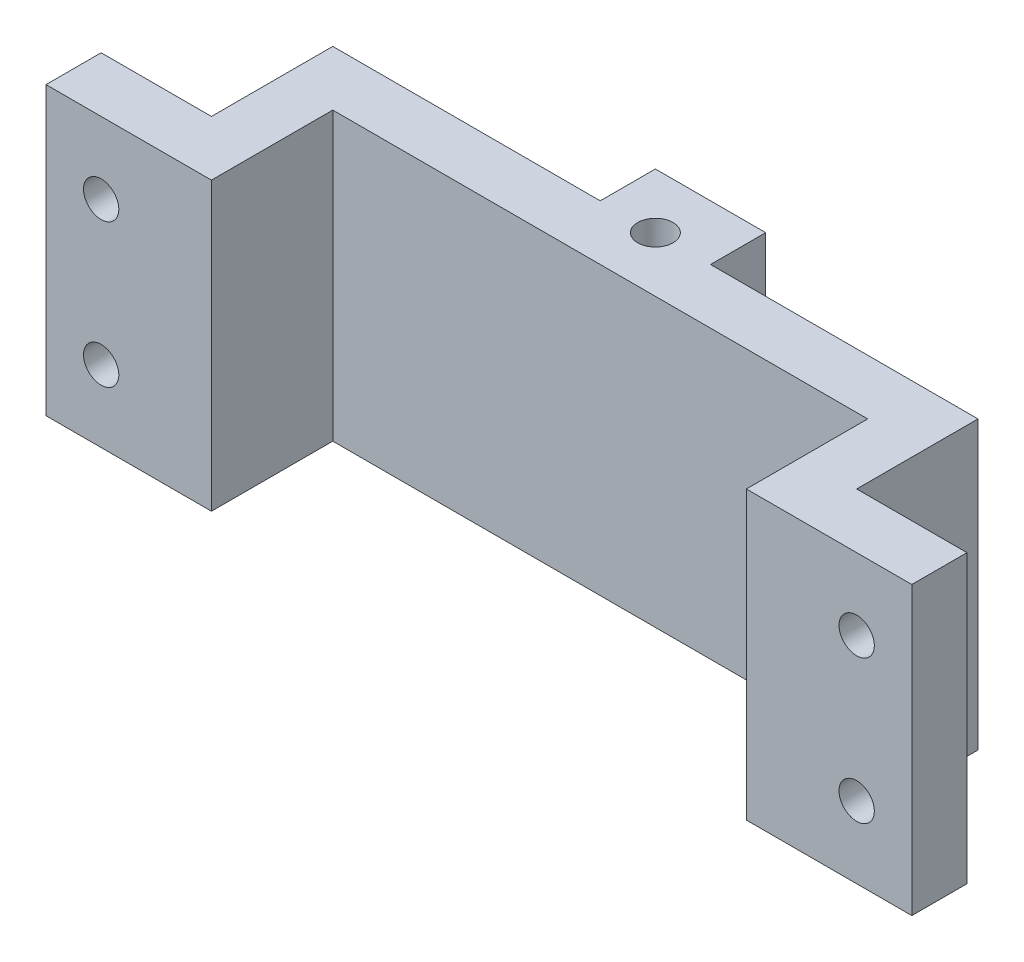
SolidWorks part; units mm, degrees
ref_plane "Front Plane" through (0, 0, 0) normal (0, 0, 1) x (1, 0, 0)
ref_plane "Top Plane" through (0, 0, 0) normal (0, 1, 0) x (1, 0, 0)
ref_plane "Right Plane" through (0, 0, 0) normal (1, 0, 0) x (0, 0, -1)
sketch "Sketch1" plane through (0, 0, 0) normal (0, 1, 0) x (1, 0, 0)
  line L0 (-24.25, 0) -> (24.25, 0)
  line L1 (24.25, 0) -> (24.25, -11)
  line L2 (24.25, -11) -> (39.25, -11)
  line L3 (39.25, -11) -> (39.25, -6)
  line L4 (39.25, -6) -> (29.25, -6)
  line L5 (29.25, -6) -> (29.25, 5)
  line L6 (29.25, 5) -> (5, 5)
  line L7 (5, 5) -> (5, 10)
  line L8 (5, 10) -> (-5, 10)
  line L9 (-5, 5) -> (-5, 10)
  line L10 (-29.25, 5) -> (-5, 5)
  line L11 (-29.25, -6) -> (-29.25, 5)
  line L12 (0, 63.1203) -> (0, -63.1203) construction
  line L13 (-39.25, -6) -> (-29.25, -6)
  line L14 (-39.25, -11) -> (-39.25, -6)
  line L15 (-24.25, -11) -> (-39.25, -11)
  line L16 (-24.25, 0) -> (-24.25, -11)
  point P0 (0, 0)
  point P10 (0, 10)
  point P14 (0, 0)
  point P22 (0, 0)
  dimension "D1" = 5
  dimension "D2" = 5
  dimension "D3" = 5
  dimension "D4" = 11
  dimension "D5" = 5
  dimension "D6" = 24.25
  dimension "D7" = 15
  dimension "D8" = 10
extrude "Boss-Extrude2" add sketch "Sketch1" along normal blind 26
sketch "Sketch5" plane through (0, 0, 0) normal (0, -1, 0) x (1, 0, 0)
  line L0 (0, 0) -> (0, -10) construction
  line L1 (5, -10) -> (-5, -10) construction
  circle A0 centre (0, -5) radius 1.6
  dimension "D1" = 3.2
extrude "Cut-Extrude4" cut sketch "Sketch5" against normal blind 26
sketch "Sketch6" plane through (0, 0, 6) normal (0, 0, -1) x (-1, 0, 0)
  line L0 (39.25, 13) -> (29.25, 13) construction
  line L1 (39.25, 26) -> (39.25, 0) construction
  line L2 (29.25, 26) -> (29.25, 0) construction
  line L3 (29.25, 13) -> (39.25, 26) construction
  line L4 (39.25, 13) -> (29.25, 26) construction
  line L6 (0, 27.3999) -> (0, 1.4654) construction
  circle A0 centre (34.25, 19.5) radius 1.6
  circle A1 centre (34.25, 6.5) radius 1.6
  circle A2 centre (-34.25, 6.5) radius 1.6
  circle A3 centre (-34.25, 19.5) radius 1.6
  dimension "D1" = 3.2
extrude "Cut-Extrude6" cut sketch "Sketch6" against normal blind 26
